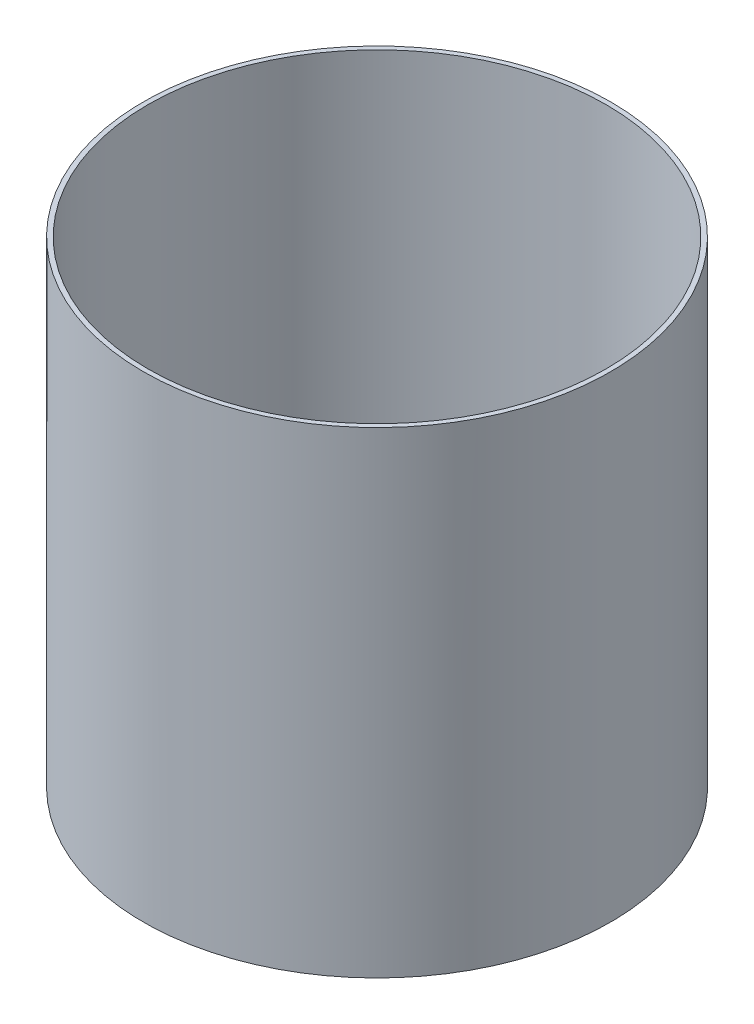
SolidWorks part; units mm, degrees
material "Glass"
ref_plane "Front Plane" through (0, 0, 0) normal (0, 0, 1) x (1, 0, 0)
ref_plane "Top Plane" through (0, 0, 0) normal (0, 1, 0) x (1, 0, 0)
ref_plane "Right Plane" through (0, 0, 0) normal (1, 0, 0) x (0, 0, -1)
sketch "Sketch1" plane through (0, 0, 0) normal (0, 1, 0) x (1, 0, 0)
  circle A0 centre (0, 0) radius 50
  circle A1 centre (0, 0) radius 49
  dimension "D1" = 1
  dimension "D2" = 100
extrude "Boss-Extrude1" add sketch "Sketch1" along normal blind 100
sketch "Sketch2" plane through (0, 0, 0) normal (0, -1, 0) x (1, 0, 0)
  circle A0 centre (0, 0) radius 50
extrude "Boss-Extrude2" add sketch "Sketch2" along normal blind 2
